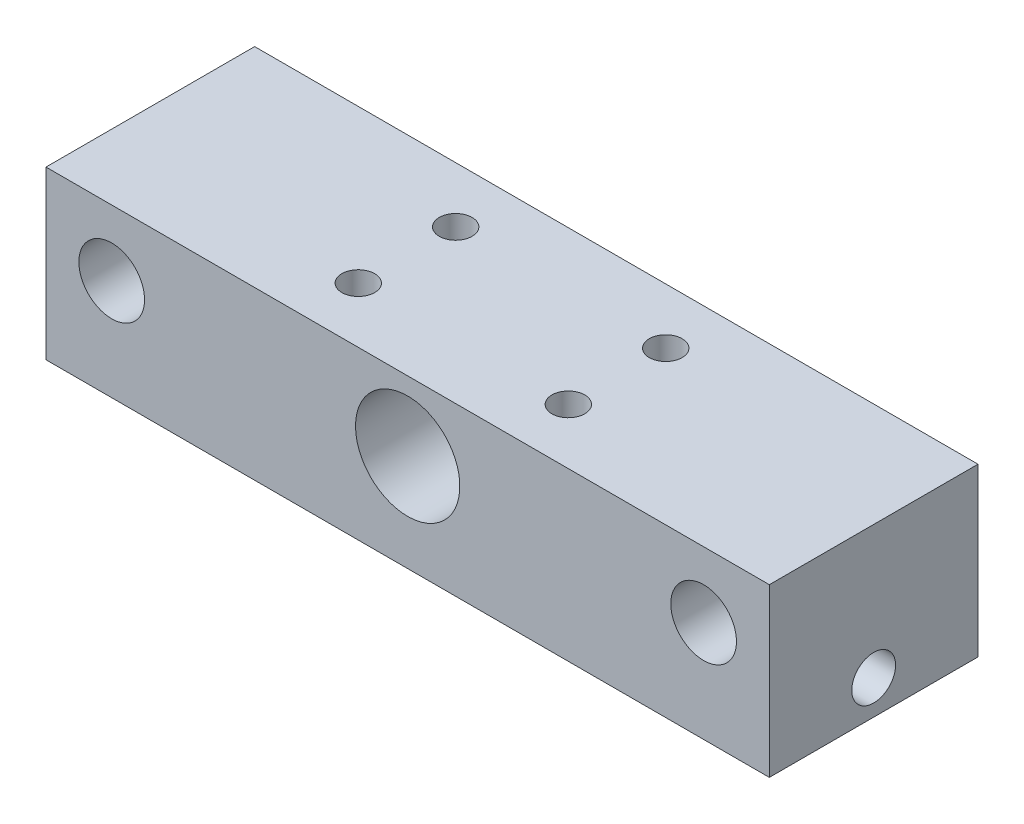
SolidWorks part; units mm, degrees
ref_plane "Front Plane" through (0, 0, 0) normal (0, 0, 1) x (1, 0, 0)
ref_plane "Top Plane" through (0, 0, 0) normal (0, 1, 0) x (1, 0, 0)
ref_plane "Right Plane" through (0, 0, 0) normal (1, 0, 0) x (0, 0, -1)
sketch "Sketch1" plane through (0, 0, 0) normal (0, 0, 1) x (1, 0, 0)
  line L0 (-27.0205, -2.6492) -> (-27.0205, -8.89)
  line L1 (-33.02, 6.35) -> (33.02, 6.35)
  line L2 (-33.02, 6.35) -> (-33.02, -6.35)
  line L3 (-33.02, -6.35) -> (33.02, -6.35)
  line L4 (33.02, 6.35) -> (33.02, -6.35)
  line L5 (-33.02, 6.35) -> (33.02, -6.35) construction
  line L6 (-33.02, -6.35) -> (33.02, 6.35) construction
  line L7 (-33.02, -6.35) -> (33.02, -6.35)
  line L8 (-33.02, -6.35) -> (-33.02, -8.89)
  line L9 (-33.02, -8.89) -> (33.02, -8.89)
  line L10 (33.02, -6.35) -> (33.02, -8.89)
  line L11 (0, -8.89) -> (0, 6.35) construction
  circle A0 centre (0, 0) radius 4.7625
  circle A1 centre (-27.0205, 0.3505) radius 2.9997
  circle A2 centre (-27.0205, -5.7696) radius 2.0002
  circle A3 centre (27.0205, 0.3505) radius 2.9997
  point P0 (0, 0)
  point P15 (-27.0205, -5.7696)
  dimension "D3" = 9.525
  dimension "D4" = 5.9995
  dimension "D9" = 4.0005
  dimension "D1" = 12.7
  dimension "D2" = 66.04
  dimension "D5" = 5.9995
  dimension "D6" = 5.9995
  dimension "D7" = 2.54
  dimension "D8" = 66.04
extrude "Boss-Extrude1" add sketch "Sketch1" along normal blind 19.05
sketch "Sketch2" plane through (-33.02, 0, 0) normal (-1, 0, 0) x (0, 0, 1)
  line L0 (0, -5.7696) -> (19.05, -5.7696)
  line L1 (19.05, 6.35) -> (19.05, -8.89) construction
  circle A0 centre (9.525, -5.7696) radius 2.0002
  point P0 (0, -5.7696)
  point P9 (9.525, -5.7696)
  dimension "D1" = 4.0005
extrude "Cut-Extrude2" cut sketch "Sketch2" against normal blind 19.05 contours L0 A0 | L0 A0
sketch "Sketch3" plane through (33.02, 0, 0) normal (1, 0, 0) x (0, 0, -1)
  circle A0 centre (-9.525, -5.7696) radius 2.0002 construction
  circle A1 centre (-9.525, -5.7696) radius 2.0002
extrude "Cut-Extrude3" cut sketch "Sketch3" against normal blind 19.05
sketch "Sketch4" plane through (0, 6.35, 0) normal (0, 1, 0) x (1, 0, 0)
  line L0 (24.0208, -19.05) -> (30.0203, -19.05) construction
  line L1 (-4.7625, -19.05) -> (4.7625, -19.05) construction
  line L2 (-30.0203, -19.05) -> (-24.0208, -19.05) construction
  line L3 (24.0208, -19.05) -> (30.0203, -19.05)
  line L4 (-4.7625, -19.05) -> (4.7625, -19.05)
  line L5 (-30.0203, -19.05) -> (-24.0208, -19.05)
  line L6 (-24.0208, -19.05) -> (-24.0208, 0)
  line L7 (-4.7625, -19.05) -> (-4.7625, 0)
  line L8 (24.0208, -19.05) -> (24.0208, 0)
  line L9 (4.7625, -19.05) -> (4.7625, 0)
  line L10 (4.7625, -13.97) -> (24.0208, -13.97)
  line L11 (4.7625, -9.525) -> (24.0208, -9.525) construction
  line L13 (0, -19.05) -> (0, 0) construction
  circle A0 centre (9.5885, -5.08) radius 1.4986
  circle A1 centre (9.5885, -13.97) radius 1.4986
  circle A2 centre (-9.5885, -5.08) radius 1.4986
  circle A3 centre (-9.5885, -13.97) radius 1.4986
  dimension "D1" = 2.9972
  dimension "D2" = 4.445
  dimension "D3" = 4.826
extrude "Cut-Extrude4" cut sketch "Sketch4" against normal blind 10.16
